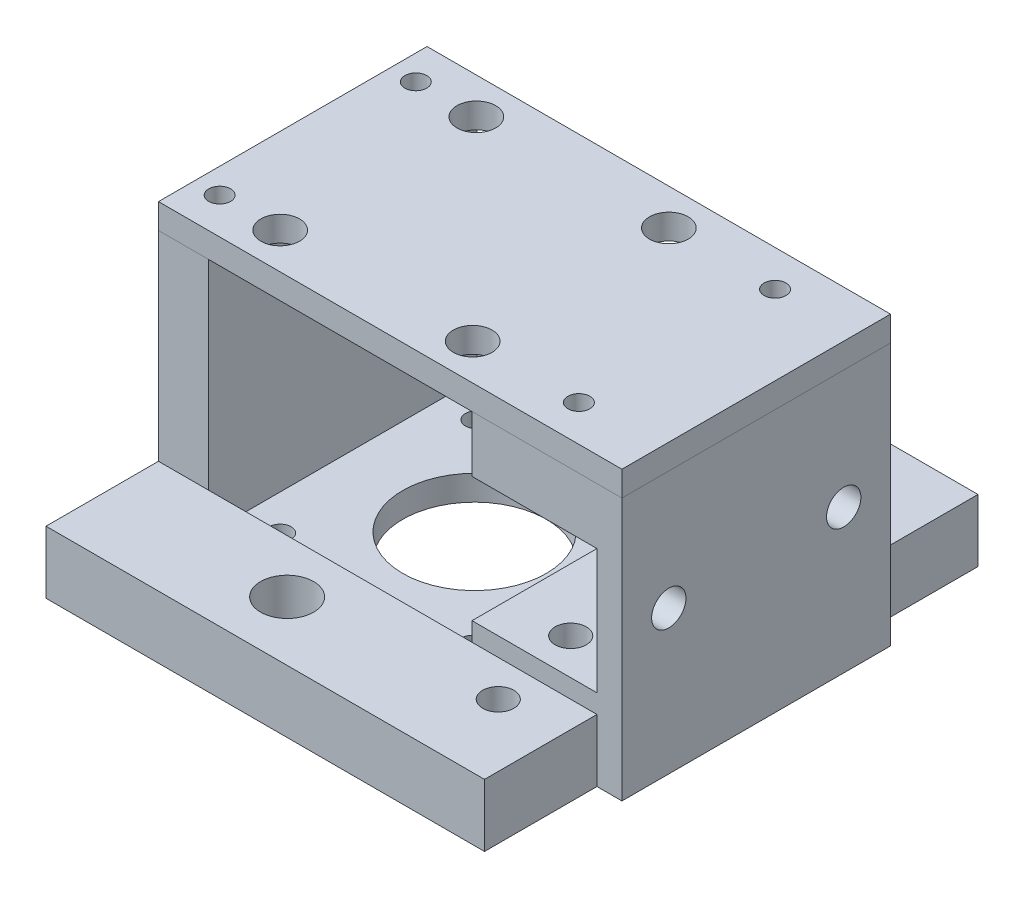
SolidWorks part; units mm, degrees
ref_plane "Front Plane" through (0, 0, 0) normal (0, 0, 1) x (1, 0, 0)
ref_plane "Top Plane" through (0, 0, 0) normal (0, 1, 0) x (1, 0, 0)
ref_plane "Right Plane" through (0, 0, 0) normal (1, 0, 0) x (0, 0, -1)
sketch "Sketch1" plane through (0, 0, 0) normal (0, 0, 1) x (1, 0, 0)
  line L1 (0, 0) -> (20, 0)
  line L3 (0, 20) -> (20, 20)
  line L4 (20, 0) -> (20, 20)
  line L6 (-50.2, 29) -> (-42.2, 29) construction
  line L11 (24, 33) -> (24, -13)
  line L12 (-42.2, -9) -> (0, -9)
  line L13 (-42.2, 29) -> (0, 29)
  line L15 (-50.2, 33) -> (-50.2, -13)
  line L16 (-50.2, 33) -> (24, 33)
  line L17 (-50.2, -13) -> (24, -13)
  line L18 (0, 29) -> (0, 20)
  line L21 (0, 0) -> (0, -9)
  line L22 (-42.2, -9) -> (-50.2, -8.4) construction
  line L24 (-42.2, 29) -> (-42.2, -9)
  dimension "D1" = 20
  dimension "D2" = 20
  dimension "D3" = 4
  dimension "D4" = 9
  dimension "D5" = 4
  dimension "D6" = 42.2
  dimension "D7" = 37.4
  dimension "D8" = 8
  dimension "D9" = 4
  dimension "D10" = 9
  dimension "D11" = 20
extrude "Boss-Extrude1" add sketch "Sketch1" along normal blind 43
sketch "Sketch2" plane through (0, -13, 0) normal (0, -1, 0) x (1, 0, 0)
  line L0 (0, 0) -> (-42.2, 43) construction
  line L1 (0, 0) -> (0, 43) construction
  line L2 (-50.2, 43) -> (24, 43) construction
  line L3 (0, 43) -> (-42.2, 0) construction
  line L4 (-36.5096, 37.2017) -> (-36.5096, 5.7983) construction
  line L5 (-5.6904, 5.7983) -> (-5.6904, 37.2017) construction
  line L6 (-42.2, 43) -> (-42.2, 0) construction
  line L7 (-50.2, 0) -> (24, 0) construction
  line L8 (-50.2, 43) -> (-50.2, 0) construction
  line L9 (20, 43) -> (20, 0) construction
  line L10 (24, 43) -> (24, 0) construction
  line L11 (0, 37.2017) -> (20, 37.2017) construction
  line L12 (0, 5.7983) -> (20, 5.7983) construction
  circle A0 centre (-21.1, 21.5) radius 11.5
  circle A1 centre (-36.5096, 37.2017) radius 1.75
  circle A2 centre (-5.6904, 5.7983) radius 1.75
  circle A3 centre (-36.5096, 5.7983) radius 1.75
  circle A4 centre (-5.6904, 37.2017) radius 1.75
  circle A7 centre (10, 37.2017) radius 2.5
  circle A8 centre (10, 5.7983) radius 2.5
  point P11 (-36.5096, 37.2017)
  point P12 (-5.6904, 5.7983)
  dimension "D1" = 23
  dimension "D4" = 3.5
  dimension "D5" = 3.5
  dimension "D6" = 3.5
  dimension "D7" = 3.5
  dimension "D9" = 4
  dimension "D10" = 5
  dimension "D11" = 5
  dimension "D2" = 22
  dimension "D3" = 22
  dimension "D8" = 8
extrude "Cut-Extrude1" cut sketch "Sketch2" against normal blind 20
sketch "Sketch3" plane through (0, 33, 0) normal (0, 1, 0) x (1, 0, 0)
  line L0 (0, 0) -> (0, -43) construction
  line L1 (24, -43) -> (-50.2, -43) construction
  line L2 (-42.2, 0) -> (0, -43) construction
  line L3 (0, 0) -> (-42.2, -43) construction
  line L4 (-36.5096, -5.7983) -> (-36.5096, -37.2017) construction
  line L5 (-36.5096, -37.2017) -> (-5.6904, -37.2017) construction
  line L6 (-5.6904, -5.7983) -> (-5.6904, -37.2017) construction
  line L7 (-36.5096, -5.7983) -> (-5.6904, -5.7983) construction
  line L8 (-42.2, 0) -> (-42.2, -43) construction
  line L9 (24, 0) -> (-50.2, 0) construction
  line L10 (-50.2, -43) -> (-50.2, 0) construction
  line L11 (-42.2, -5.7983) -> (-50.2, -5.7983) construction
  line L12 (-42.2, -37.2017) -> (-50.2, -37.2017) construction
  line L13 (0, -5.7983) -> (24, -5.7983) construction
  line L14 (24, -43) -> (24, 0) construction
  line L15 (0, -37.2017) -> (24, -37.2017) construction
  line L16 (11.3096, -5.7983) -> (11.3096, -37.2017) construction
  circle A0 centre (-36.5096, -5.7983) radius 3.1
  circle A1 centre (-5.6904, -5.7983) radius 3.1
  circle A2 centre (-5.6904, -37.2017) radius 3.1
  circle A3 centre (-36.5096, -37.2017) radius 3.1
  circle A4 centre (-46.2, -5.7983) radius 1.75
  circle A5 centre (-46.2, -37.2017) radius 1.75
  circle A6 centre (11.3096, -5.7983) radius 1.75
  circle A7 centre (11.3096, -37.2017) radius 1.75
  point P8 (-36.5096, -5.7983)
  point P10 (-21.1, -21.5)
  dimension "D2" = 6.2
  dimension "D3" = 6.2
  dimension "D4" = 6.2
  dimension "D5" = 6.2
  dimension "D7" = 3.5
  dimension "D8" = 3.5
  dimension "D9" = 3.5
  dimension "D10" = 3.5
  dimension "D1" = 22
  dimension "D6" = 8
  dimension "D11" = 17
extrude "Cut-Extrude2" cut sketch "Sketch3" against normal blind 15
ref_plane "Plane1" through (0, 29, 0) normal (0, 1, 0) x (1, 0, 0)
split "Split1" trim tools "Plane1" bodies to split 103 resulting bodies 106 107
sketch "Sketch4" plane through (0, 29, 0) normal (0, 1, 0) x (1, 0, 0)
  line L1 (-46.2, -2.3342) -> (-49.2, -4.0662)
  line L2 (-49.2, -4.0662) -> (-49.2, -7.5303)
  line L3 (-49.2, -7.5303) -> (-46.2, -9.2624)
  line L4 (-46.2, -9.2624) -> (-43.2, -7.5303)
  line L5 (-43.2, -7.5303) -> (-43.2, -4.0662)
  line L6 (-43.2, -4.0662) -> (-46.2, -2.3342)
  line L7 (-43.2, -35.4697) -> (-46.2, -33.7376)
  line L8 (-46.2, -33.7376) -> (-49.2, -35.4697)
  line L9 (-49.2, -35.4697) -> (-49.2, -38.9338)
  line L10 (-49.2, -38.9338) -> (-46.2, -40.6658)
  line L11 (-46.2, -40.6658) -> (-43.2, -38.9338)
  line L12 (-43.2, -38.9338) -> (-43.2, -35.4697)
  line L13 (14.3096, -4.0662) -> (11.3096, -2.3342)
  line L14 (11.3096, -2.3342) -> (8.3096, -4.0662)
  line L15 (8.3096, -4.0662) -> (8.3096, -7.5303)
  line L16 (8.3096, -7.5303) -> (11.3096, -9.2624)
  line L17 (11.3096, -9.2624) -> (14.3096, -7.5303)
  line L18 (14.3096, -7.5303) -> (14.3096, -4.0662)
  line L19 (14.3096, -35.4697) -> (11.3096, -33.7376)
  line L20 (11.3096, -33.7376) -> (8.3096, -35.4697)
  line L21 (8.3096, -35.4697) -> (8.3096, -38.9338)
  line L22 (8.3096, -38.9338) -> (11.3096, -40.6658)
  line L23 (11.3096, -40.6658) -> (14.3096, -38.9338)
  line L24 (14.3096, -38.9338) -> (14.3096, -35.4697)
  circle A0 centre (-46.2, -5.7983) radius 3 construction
  circle A1 centre (-46.2, -37.2017) radius 3 construction
  circle A2 centre (11.3096, -5.7983) radius 3 construction
  circle A3 centre (11.3096, -37.2017) radius 3 construction
  point P10 (-47.7, -39.7998)
  point P29 (9.8096, -8.3964)
  dimension "D1" = 6
  dimension "D2" = 6
  dimension "D3" = 6
  dimension "D4" = 6
extrude "Cut-Extrude3" cut sketch "Sketch4" against normal blind 2.4
sketch "Sketch5" plane through (24, 0, 0) normal (1, 0, 0) x (0, 0, -1)
  line L0 (0, 0) -> (-43, 0) construction
  line L1 (-43, -13) -> (-43, 29) construction
  line L2 (-43, 20) -> (0, 20) construction
  line L3 (0, -13) -> (0, 29) construction
  line L4 (-21.5, 20) -> (-21.5, 0) construction
  line L5 (-43, 10) -> (0, 10) construction
  circle A0 centre (-35.5, 10) radius 2.75
  circle A1 centre (-7.5, 10) radius 2.75
  point P17 (-21.5, 10)
  dimension "D2" = 5.5
  dimension "D3" = 5.5
  dimension "D1" = 20
extrude "Cut-Extrude4" cut sketch "Sketch5" against normal blind 12.4
sketch "Sketch7" plane through (0, -13, 0) normal (0, -1, 0) x (1, 0, 0)
  line L0 (0, 0) -> (20, 0) construction
  line L1 (20, 0) -> (20, 43) construction
  line L2 (20, 43) -> (0, 43) construction
  line L3 (0, 43) -> (0, 0) construction
  line L4 (-50.2, 0) -> (24, 0) construction
  line L5 (24, 0) -> (24, 43) construction
  line L6 (24, 43) -> (-50.2, 43) construction
  line L7 (-50.2, 43) -> (-50.2, 0) construction
  line L8 (0, 0) -> (20, 0)
  line L9 (20, 0) -> (20, 43)
  line L10 (20, 43) -> (0, 43)
  line L11 (0, 43) -> (0, 0)
  line L12 (-50.2, 0) -> (24, 0)
  line L13 (24, 0) -> (24, 43)
  line L14 (24, 43) -> (-50.2, 43)
  line L15 (-50.2, 43) -> (-50.2, 0)
  line L16 (-21.1, 21.5) -> (-21.1, 82.9062) construction
  line L17 (-21.1, 21.5) -> (-72.7741, 21.5) construction
  line L18 (20, 0) -> (20, -18)
  line L19 (-50.2, 43) -> (0, 43)
  line L23 (-50.2, 43) -> (20, 43)
  line L24 (-50.2, 0) -> (0, 0)
  line L25 (24, 0) -> (-50.2, 0)
  line L29 (-50.2, 43) -> (-50.2, 61)
  line L30 (-50.2, 61) -> (20, 61)
  line L31 (20, 43) -> (20, 61)
  line L32 (-50.2, 0) -> (-50.2, -18)
  line L33 (-50.2, -18) -> (20, -18)
  circle A0 centre (-5.6904, 37.2017) radius 1.75 construction
  circle A1 centre (-5.6904, 5.7983) radius 1.75 construction
  circle A2 centre (-36.5096, 5.7983) radius 1.75 construction
  circle A3 centre (-36.5096, 37.2017) radius 1.75 construction
  circle A4 centre (-21.1, 21.5) radius 11.5 construction
  circle A5 centre (-5.6904, 37.2017) radius 1.75
  circle A6 centre (-5.6904, 5.7983) radius 1.75
  circle A7 centre (-36.5096, 5.7983) radius 1.75
  circle A8 centre (-36.5096, 37.2017) radius 1.75
  circle A9 centre (-21.1, 21.5) radius 11.5
  circle A10 centre (-21.1, 51.5) radius 4.25
  circle A12 centre (-21.1, -8.5) radius 4.25
  circle A13 centre (10, 5.7983) radius 2.5 construction
  circle A14 centre (10, 37.2017) radius 2.5 construction
  circle A15 centre (10, 5.7983) radius 2.5
  circle A16 centre (10, 37.2017) radius 2.5
  circle A17 centre (10, 48.7983) radius 2.5
  circle A18 centre (10, -5.7983) radius 2.5
  point P23 (-21.1, 51.5)
  line M16 (-50.2, 0) -> (24, 0)
  line M18 (24, 43) -> (-50.2, 43)
  dimension "D2" = 8.5
  dimension "D1" = 30
  dimension "D3" = 18
extrude "Boss-Extrude8" add sketch "Sketch7" against normal blind 10 contours L14 L31 L30 L29 A10 M18 | L32 L33 L18 A12 M16
